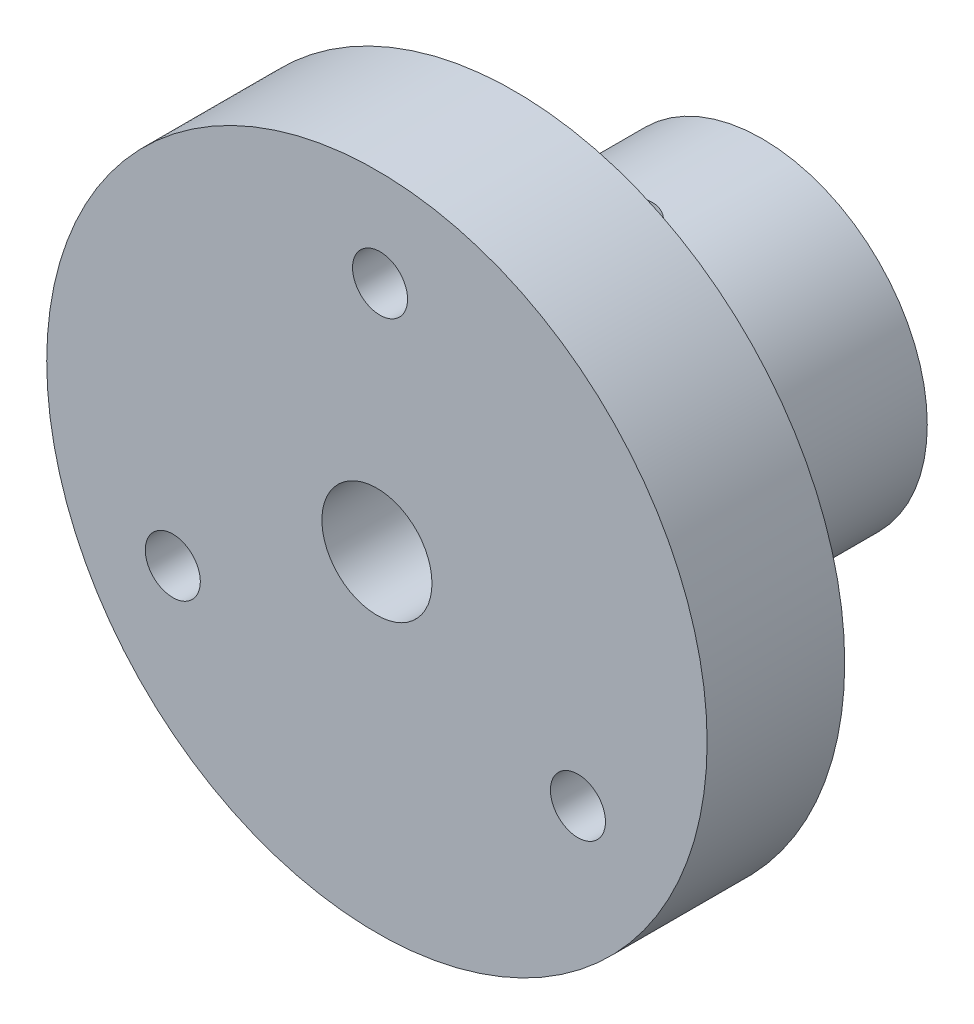
SolidWorks part; units mm, degrees
ref_plane "Front Plane" through (0, 0, 0) normal (0, 0, 1) x (1, 0, 0)
ref_plane "Top Plane" through (0, 0, 0) normal (0, 1, 0) x (1, 0, 0)
ref_plane "Right Plane" through (0, 0, 0) normal (1, 0, 0) x (0, 0, -1)
sketch "Sketch1" plane through (0, 0, 0) normal (0, 0, 1) x (1, 0, 0)
  circle A0 centre (-41.1435, 10.1614) radius 2
  circle A1 centre (-41.1435, 10.1614) radius 6
  dimension "D1" = 12
extrude "Boss-Extrude1" add sketch "Sketch1" along normal up to surface (9 mm away)
sketch "Sketch2" plane through (0, 0, 9) normal (0, 0, 1) x (1, 0, 0)
  circle A0 centre (-41.1435, 10.1614) radius 2
  circle A1 centre (-41.1435, 10.1614) radius 12
extrude "Boss-Extrude2" add sketch "Sketch2" along normal blind 5
sketch "Sketch3" plane through (0, 17.8114, 0) normal (0, 1, 0) x (1, 0, 0)
  line L0 (-35.1435, 0) -> (-47.1435, 0) construction
  circle A0 centre (-41.1435, -5) radius 1
  dimension "D2" = 2
  dimension "D1" = 5
extrude "Cut-Extrude1" cut sketch "Sketch3" against normal blind 7
sketch "Sketch4" plane through (0, 0, 14) normal (0, 0, 1) x (1, 0, 0)
  circle A1 centre (-41.0304, 18.6614) radius 1
  circle A4 centre (-33.8388, 5.8135) radius 1
  circle A5 centre (-48.5612, 6.0093) radius 1
  point P3 (-41.1435, 10.1614)
  point P10 (-41.1435, 10.1614)
  point P13 (-41.1435, 10.1614)
  point P14 (-41.1435, 10.1614)
  dimension "D1" = 8.5
  dimension "D2" = 3
  dimension "D3" = 2
extrude "Cut-Extrude2" cut sketch "Sketch4" against normal up to surface (5 mm away) up to face at (-35.1435, 10.1614, 9)
